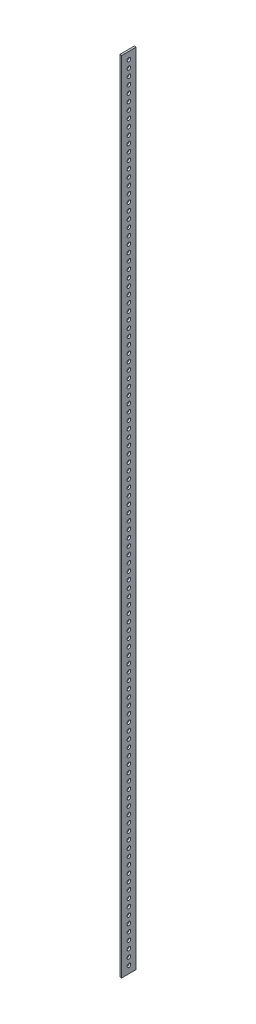
SolidWorks part; units mm, degrees
ref_plane "Front Plane" through (0, 0, 0) normal (0, 0, 1) x (1, 0, 0)
ref_plane "Top Plane" through (0, 0, 0) normal (0, 1, 0) x (1, 0, 0)
ref_plane "Right Plane" through (0, 0, 0) normal (1, 0, 0) x (0, 0, -1)
sketch "Sketch1" plane through (0, 0, 0) normal (1, 0, 0) x (0, 0, -1)
  line L1 (-12.7, -698.5) -> (12.7, -698.5)
  line L2 (-12.7, -698.5) -> (-12.7, 698.5)
  line L3 (-12.7, 698.5) -> (12.7, 698.5)
  line L4 (12.7, -698.5) -> (12.7, 698.5)
  line L5 (-12.7, -698.5) -> (12.7, 698.5) construction
  line L6 (-12.7, 698.5) -> (12.7, -698.5) construction
  circle A0 centre (0, -685.8) radius 3.175
  circle A1 centre (0, -673.1) radius 3.175
  circle A2 centre (0, -660.4) radius 3.175
  circle A3 centre (0, -647.7) radius 3.175
  circle A4 centre (0, -635) radius 3.175
  circle A5 centre (0, -622.3) radius 3.175
  circle A6 centre (0, -609.6) radius 3.175
  circle A7 centre (0, -596.9) radius 3.175
  circle A8 centre (0, -584.2) radius 3.175
  circle A9 centre (0, -571.5) radius 3.175
  circle A10 centre (0, -558.8) radius 3.175
  circle A11 centre (0, -546.1) radius 3.175
  circle A12 centre (0, -533.4) radius 3.175
  circle A13 centre (0, -520.7) radius 3.175
  circle A14 centre (0, -508) radius 3.175
  circle A15 centre (0, -495.3) radius 3.175
  circle A16 centre (0, -482.6) radius 3.175
  circle A17 centre (0, -469.9) radius 3.175
  circle A18 centre (0, -457.2) radius 3.175
  circle A19 centre (0, -444.5) radius 3.175
  circle A20 centre (0, -431.8) radius 3.175
  circle A21 centre (0, -419.1) radius 3.175
  circle A22 centre (0, -406.4) radius 3.175
  circle A23 centre (0, -393.7) radius 3.175
  circle A24 centre (0, -381) radius 3.175
  circle A25 centre (0, -368.3) radius 3.175
  circle A26 centre (0, -355.6) radius 3.175
  circle A27 centre (0, -342.9) radius 3.175
  circle A28 centre (0, -330.2) radius 3.175
  circle A29 centre (0, -317.5) radius 3.175
  circle A30 centre (0, -304.8) radius 3.175
  circle A31 centre (0, -292.1) radius 3.175
  circle A32 centre (0, -279.4) radius 3.175
  circle A33 centre (0, -266.7) radius 3.175
  circle A34 centre (0, -254) radius 3.175
  circle A35 centre (0, -241.3) radius 3.175
  circle A36 centre (0, -228.6) radius 3.175
  circle A37 centre (0, -215.9) radius 3.175
  circle A38 centre (0, -203.2) radius 3.175
  circle A39 centre (0, -190.5) radius 3.175
  circle A40 centre (0, -177.8) radius 3.175
  circle A41 centre (0, -165.1) radius 3.175
  circle A42 centre (0, -152.4) radius 3.175
  circle A43 centre (0, -139.7) radius 3.175
  circle A44 centre (0, -127) radius 3.175
  circle A45 centre (0, -114.3) radius 3.175
  circle A46 centre (0, -101.6) radius 3.175
  circle A47 centre (0, -88.9) radius 3.175
  circle A48 centre (0, -76.2) radius 3.175
  circle A49 centre (0, -63.5) radius 3.175
  circle A50 centre (0, -50.8) radius 3.175
  circle A51 centre (0, -38.1) radius 3.175
  circle A52 centre (0, -25.4) radius 3.175
  circle A53 centre (0, -12.7) radius 3.175
  circle A54 centre (0, 0) radius 3.175
  circle A55 centre (0, 12.7) radius 3.175
  circle A56 centre (0, 25.4) radius 3.175
  circle A57 centre (0, 38.1) radius 3.175
  circle A58 centre (0, 50.8) radius 3.175
  circle A59 centre (0, 63.5) radius 3.175
  circle A60 centre (0, 76.2) radius 3.175
  circle A61 centre (0, 88.9) radius 3.175
  circle A62 centre (0, 101.6) radius 3.175
  circle A63 centre (0, 114.3) radius 3.175
  circle A64 centre (0, 127) radius 3.175
  circle A65 centre (0, 139.7) radius 3.175
  circle A66 centre (0, 152.4) radius 3.175
  circle A67 centre (0, 165.1) radius 3.175
  circle A68 centre (0, 177.8) radius 3.175
  circle A69 centre (0, 190.5) radius 3.175
  circle A70 centre (0, 203.2) radius 3.175
  circle A71 centre (0, 215.9) radius 3.175
  circle A72 centre (0, 228.6) radius 3.175
  circle A73 centre (0, 241.3) radius 3.175
  circle A74 centre (0, 254) radius 3.175
  circle A75 centre (0, 266.7) radius 3.175
  circle A76 centre (0, 279.4) radius 3.175
  circle A77 centre (0, 292.1) radius 3.175
  circle A78 centre (0, 304.8) radius 3.175
  circle A79 centre (0, 317.5) radius 3.175
  circle A80 centre (0, 330.2) radius 3.175
  circle A81 centre (0, 342.9) radius 3.175
  circle A82 centre (0, 355.6) radius 3.175
  circle A83 centre (0, 368.3) radius 3.175
  circle A84 centre (0, 381) radius 3.175
  circle A85 centre (0, 393.7) radius 3.175
  circle A86 centre (0, 406.4) radius 3.175
  circle A87 centre (0, 419.1) radius 3.175
  circle A88 centre (0, 431.8) radius 3.175
  circle A89 centre (0, 444.5) radius 3.175
  circle A90 centre (0, 457.2) radius 3.175
  circle A91 centre (0, 469.9) radius 3.175
  circle A92 centre (0, 482.6) radius 3.175
  circle A93 centre (0, 495.3) radius 3.175
  circle A94 centre (0, 508) radius 3.175
  circle A95 centre (0, 520.7) radius 3.175
  circle A96 centre (0, 533.4) radius 3.175
  circle A97 centre (0, 546.1) radius 3.175
  circle A98 centre (0, 558.8) radius 3.175
  circle A99 centre (0, 571.5) radius 3.175
  circle A100 centre (0, 584.2) radius 3.175
  circle A101 centre (0, 596.9) radius 3.175
  circle A102 centre (0, 609.6) radius 3.175
  circle A103 centre (0, 622.3) radius 3.175
  circle A104 centre (0, 635) radius 3.175
  circle A105 centre (0, 647.7) radius 3.175
  circle A106 centre (0, 660.4) radius 3.175
  circle A107 centre (0, 673.1) radius 3.175
  circle A108 centre (0, 685.8) radius 3.175
  point P0 (0, 0)
  dimension "D1" = 109
extrude "Boss-Extrude1" add sketch "Sketch1" along normal blind 3.175
